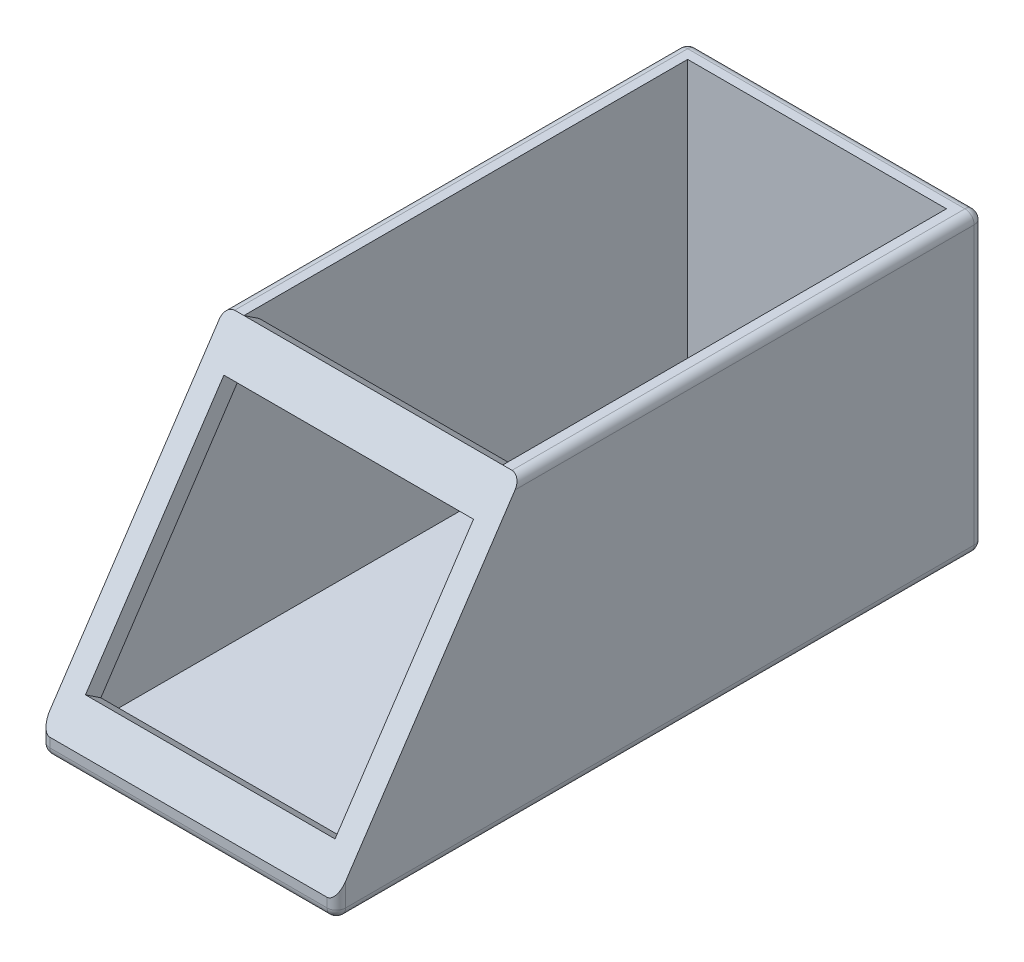
SolidWorks part; units mm, degrees
ref_plane "Front Plane" through (0, 0, 0) normal (0, 0, 1) x (1, 0, 0)
ref_plane "Top Plane" through (0, 0, 0) normal (0, 1, 0) x (1, 0, 0)
ref_plane "Right Plane" through (0, 0, 0) normal (1, 0, 0) x (0, 0, -1)
sketch "Sketch2" plane through (0, 0, 0) normal (0, 1, 0) x (1, 0, 0)
  line L0 (0, 0) -> (0, 45.4191) construction
  line L1 (-16, 35) -> (16, 35)
  line L2 (-16, 35) -> (-16, -35)
  line L3 (-16, -35) -> (16, -35)
  line L4 (16, 35) -> (16, -35)
  line L5 (-16, 35) -> (16, -35) construction
  line L6 (-16, -35) -> (16, 35) construction
  point P0 (0, 0)
  point P8 (0, 0)
  dimension "D1" = 70
  dimension "D2" = 32
extrude "Boss-Extrude1" add sketch "Sketch2" along normal blind 2
sketch "Sketch4" plane through (-16, 0, 0) normal (-1, 0, 0) x (0, 0, 1)
  line L0 (35, 2) -> (15, 32)
  line L1 (-35, 2) -> (35, 2)
  line L2 (-35, 2) -> (-35, 32)
  line L3 (-35, 32) -> (15, 32)
  dimension "D1" = 50
  dimension "D2" = 36.0555
  dimension "D3" = 70
extrude "Boss-Extrude2" add sketch "Sketch4" against normal blind 2 separate body contours L1 L2 L3 L0
sketch "Sketch5" plane through (16, 0, 0) normal (1, 0, 0) x (0, 0, -1)
  line L0 (-35, 2) -> (-15, 32)
  line L1 (-35, 2) -> (35, 2)
  line L3 (-15, 32) -> (35, 32)
  line L4 (35, 2) -> (35, 32)
extrude "Boss-Extrude3" add sketch "Sketch5" against normal blind 2 separate body contours L0 L3 L4 L1
sketch "Sketch6" plane through (0, 0, -35) normal (0, 0, -1) x (-1, 0, 0)
  line L1 (-14, 2) -> (14, 2)
  line L2 (-14, 2) -> (-14, 32)
  line L3 (-14, 32) -> (14, 32)
  line L4 (14, 2) -> (14, 32)
extrude "Boss-Extrude4" add sketch "Sketch6" against normal blind 2 contours L2 L1 L4 L3
fillet "Fillet1" radius 1 1 edges at (16, 32, -10)
fillet "Fillet2" radius 1 1 edges at (-16, 32, -10)
fillet "Fillet3" radius 1 5 edges at (16, 15.5, -35) (15.7071, 31.7071, -35) (-16, 15.5, -35) (-15.7071, 31.7071, -35) (0, 32, -35)
fillet "Fillet4" radius 1 5 edges at (-16, 0, 0.5) (-15.7071, 0, -34.7071) (0, 0, -35) (15.7071, 0, -34.7071) (16, 0, 0.5)
fillet "Fillet5" radius 1 5 edges at (-16, 1.5, 35) (-15.7071, 0.2929, 35) (16, 1.5, 35) (15.7071, 0.2929, 35) (0, 0, 35)
sketch "Sketch7" plane through (0, 16.7692, 25.1538) normal (0, 0.5547, 0.8321) x (1, 0, 0)
  line L1 (-14, 18.3051) -> (14, 18.3051)
  line L2 (-14, 18.3051) -> (-14, -17.7504)
  line L3 (-14, -17.7504) -> (14, -17.7504)
  line L4 (14, 18.3051) -> (14, -17.7504)
  line L5 (-13.5, 13.5) -> (13.5, 13.5)
  line L6 (-13.5, 13.5) -> (-13.5, -13.5)
  line L7 (-13.5, -13.5) -> (13.5, -13.5)
  line L8 (13.5, 13.5) -> (13.5, -13.5)
  line L9 (-13.5, 13.5) -> (13.5, -13.5) construction
  line L10 (-13.5, -13.5) -> (13.5, 13.5) construction
  point P4 (0, 0)
  dimension "D1" = 27
  dimension "D2" = 27
extrude "Boss-Extrude5" add sketch "Sketch7" against normal blind 2
